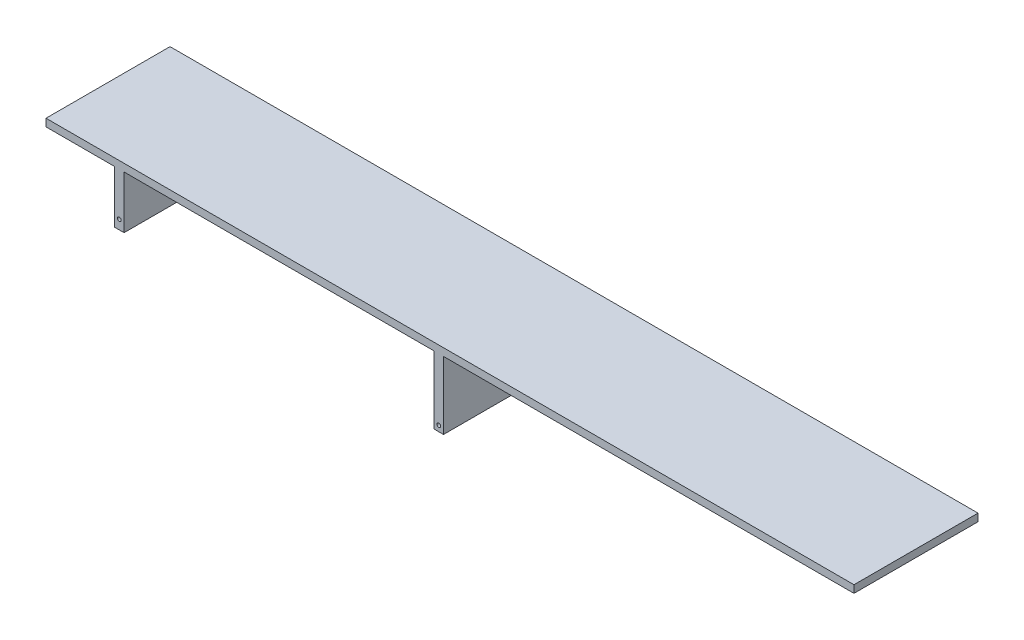
SolidWorks part; units mm, degrees
ref_plane "Plan de face" through (0, 0, 0) normal (0, 0, 1) x (1, 0, 0)
ref_plane "Plan de dessus" through (0, 0, 0) normal (0, 1, 0) x (1, 0, 0)
ref_plane "Plan de droite" through (0, 0, 0) normal (1, 0, 0) x (0, 0, -1)
sketch "Esquisse1" plane through (0, 0, 0) normal (0, 0, 1) x (1, 0, 0)
  line L0 (-60.6163, 24.5802) -> (-24.0701, 24.5802)
  line L1 (-60.6163, 28.5802) -> (369.3837, 28.5802)
  line L2 (-60.6163, 28.5802) -> (-60.6163, 24.5802)
  line L3 (-19.0701, 24.5802) -> (145.9299, 24.5802)
  line L4 (369.3837, 28.5802) -> (369.3837, 24.5802)
  line L6 (145.9299, 24.5802) -> (145.9299, -11.4198)
  line L7 (145.9299, -11.4198) -> (150.9299, -11.4198)
  line L8 (150.9299, 24.5802) -> (150.9299, -11.4198)
  line L9 (150.9299, 24.5802) -> (369.3837, 24.5802)
  line L10 (-24.0701, 24.5802) -> (-24.0701, -3.4198)
  line L11 (-24.0701, -3.4198) -> (-19.0701, -3.4198)
  line L12 (-19.0701, 24.5802) -> (-19.0701, -3.4198)
  circle A0 centre (148.4299, -8.4198) radius 1
  circle A1 centre (-21.5701, 1.5802) radius 1
  dimension "D8" = 2
  dimension "D10" = 2
  dimension "D1" = 430
  dimension "D2" = 4
  dimension "D3" = 5
  dimension "D4" = 40
  dimension "D5" = 5
  dimension "D6" = 32
  dimension "D7" = 175
  dimension "D9" = 2.5
  dimension "D11" = 2.5
  dimension "D12" = 37
  dimension "D13" = 27
extrude "Boss.-Extru.1" add sketch "Esquisse1" along normal blind 66
